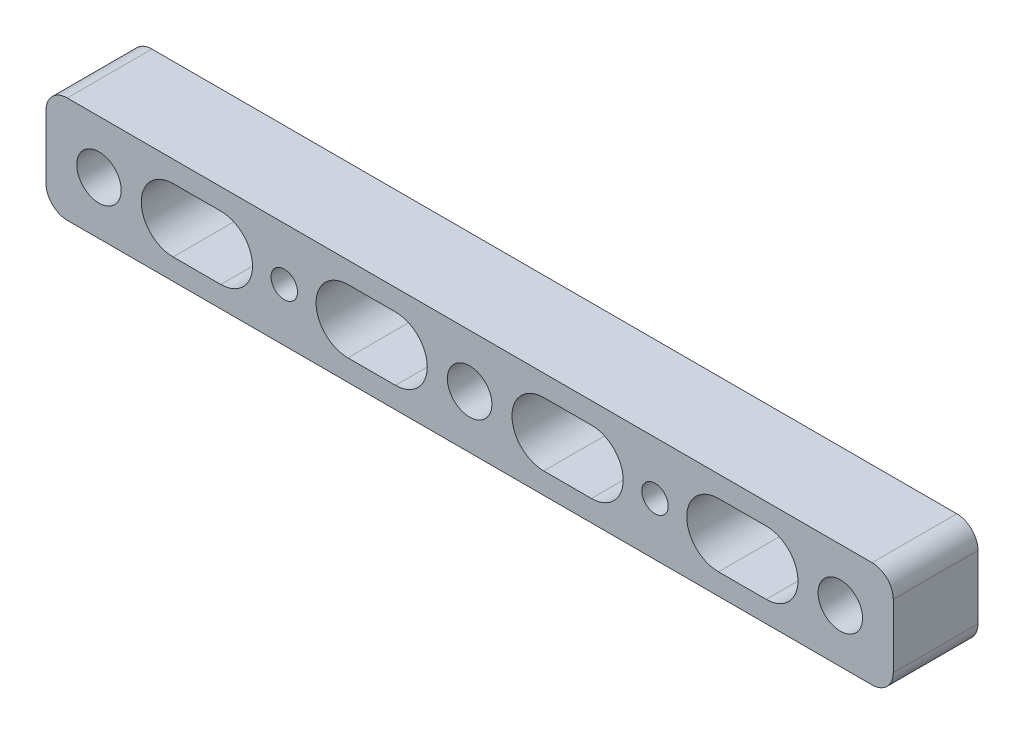
SolidWorks part; units mm, degrees
material "6061 合金"
ref_plane "前视基准面" through (0, 0, 0) normal (0, 0, 1) x (1, 0, 0)
ref_plane "上视基准面" through (0, 0, 0) normal (0, 1, 0) x (1, 0, 0)
ref_plane "右视基准面" through (0, 0, 0) normal (1, 0, 0) x (0, 0, -1)
other "Configuration Table"
sketch "草图1" plane through (0, 0, 0) normal (0, 0, 1) x (1, 0, 0)
  line L1 (-40, -5) -> (40, -5)
  line L2 (-40, -5) -> (-40, 5)
  line L3 (-40, 5) -> (40, 5)
  line L4 (40, -5) -> (40, 5)
  line L5 (-40, -5) -> (40, 5) construction
  line L6 (-40, 5) -> (40, -5) construction
  point P0 (0, 0)
  dimension "D1" = 80
  dimension "D2" = 10
extrude "凸台-拉伸1" add sketch "草图1" along normal blind 8
sketch "草图2" plane through (0, 0, 8) normal (0, 0, 1) x (1, 0, 0)
  line L0 (-35, 0) -> (35, 0) construction
  point P4 (0, 0)
  dimension "D1" = 70
hole_wizard "M5 螺纹孔1" positions "草图3" profile "草图4" tap size "M5" standard "GB"
sketch "草图3" plane through (0, 0, 8) normal (0, 0, 1) x (1, 0, 0)
  point P0 (-35, 0)
  point P3 (0, 0)
  point P6 (35, 0)
sketch "草图4" plane through (-35, 0, 8) normal (1, 0, 0) x (0, -1, 0)
  line L0 (0, 0) -> (0, 13.6618)
  line L1 (0, 13.6618) -> (2.1, 12.4)
  line L2 (2.1, 12.4) -> (2.1, 0)
  line L5 (2.1, 0) -> (0, 0)
  line L10 (0, 13.6618) -> (-2.1, 12.4) construction
  line L11 (0, -6.35) -> (0, 107.95) construction
  dimension "螺纹孔钻头直径" = 4.2
  dimension "螺纹孔钻头深度" = 12.4
  dimension "导头角度" = 118
cosmetic thread "孔螺蚊线1" parameters "D1"=10, "D2"=5
cosmetic thread "孔螺蚊线2" parameters "D1"=10, "D2"=5
cosmetic thread "孔螺蚊线3" parameters "D1"=10, "D2"=5
sketch "草图5" plane through (0, 0, 8) normal (0, 0, 1) x (1, 0, 0)
  line L0 (-35, 0) -> (0, 0) construction
  line L1 (0, 0) -> (35, 0) construction
hole_wizard "M3 螺纹孔1" positions "草图6" profile "草图7" tap size "M3" standard "GB"
sketch "草图6" plane through (0, 0, 8) normal (0, 0, 1) x (1, 0, 0)
  line L0 (-35, 0) -> (0, 0) construction
  line L1 (0, 0) -> (35, 0) construction
  point P0 (-17.5, 0)
  point P4 (17.5, 0)
sketch "草图7" plane through (-17.5, 0, 8) normal (1, 0, 0) x (0, -1, 0)
  line L0 (0, 0) -> (0, 18.2511)
  line L1 (0, 18.2511) -> (1.25, 17.5)
  line L2 (1.25, 17.5) -> (1.25, 0)
  line L5 (1.25, 0) -> (0, 0)
  line L10 (0, 18.2511) -> (-1.25, 17.5) construction
  line L11 (0, -6.35) -> (0, 107.95) construction
  dimension "螺纹孔钻头直径" = 2.5
  dimension "螺纹孔钻头深度" = 17.5
  dimension "导头角度" = 118
cosmetic thread "孔螺蚊线4" parameters "D1"=16, "D2"=3
cosmetic thread "孔螺蚊线5" parameters "D1"=16, "D2"=3
fillet "圆角1" radius 2 4 edges at (40, -5, 4) (40, 5, 4) (-40, 5, 4) (-40, -5, 4)
sketch "草图8" plane through (0, 0, 8) normal (0, 0, 1) x (1, 0, 0)
  line L0 (-35, 0) -> (-17.5, 0) construction
  line L1 (-28, 0) -> (-23.5, 0) construction
  line L2 (-28, 3) -> (-23.5, 3)
  line L3 (-28, -3) -> (-23.5, -3)
  line L4 (38, 5) -> (-38, 5) construction
  line L5 (-17.5, 0) -> (-17.5, 5) construction
  line L6 (-7, 0) -> (-11.5, 0) construction
  line L7 (-7, 3) -> (-11.5, 3)
  line L8 (-7, -3) -> (-11.5, -3)
  line L9 (0, 0) -> (0, 5) construction
  line L10 (7, 0) -> (11.5, 0) construction
  line L11 (7, 3) -> (11.5, 3)
  line L12 (7, -3) -> (11.5, -3)
  line L13 (28, 0) -> (23.5, 0) construction
  line L14 (28, 3) -> (23.5, 3)
  line L15 (28, -3) -> (23.5, -3)
  arc A0 (-28, 3) -> (-28, -3) centre (-28, 0) ccw
  arc A1 (-23.5, -3) -> (-23.5, 3) centre (-23.5, 0) ccw
  arc A2 (-7, 3) -> (-7, -3) centre (-7, 0) cw
  arc A3 (-11.5, -3) -> (-11.5, 3) centre (-11.5, 0) cw
  arc A4 (7, 3) -> (7, -3) centre (7, 0) ccw
  arc A5 (11.5, -3) -> (11.5, 3) centre (11.5, 0) ccw
  arc A6 (28, 3) -> (28, -3) centre (28, 0) cw
  arc A7 (23.5, -3) -> (23.5, 3) centre (23.5, 0) cw
  point P6 (-25.75, 0)
  point P16 (-9.25, 0)
  point P26 (9.25, 0)
  point P33 (25.75, 0)
  dimension "D1" = 6
  dimension "D2" = 7
  dimension "D3" = 2
extrude "切除-拉伸1" cut sketch "草图8" against normal blind 36
